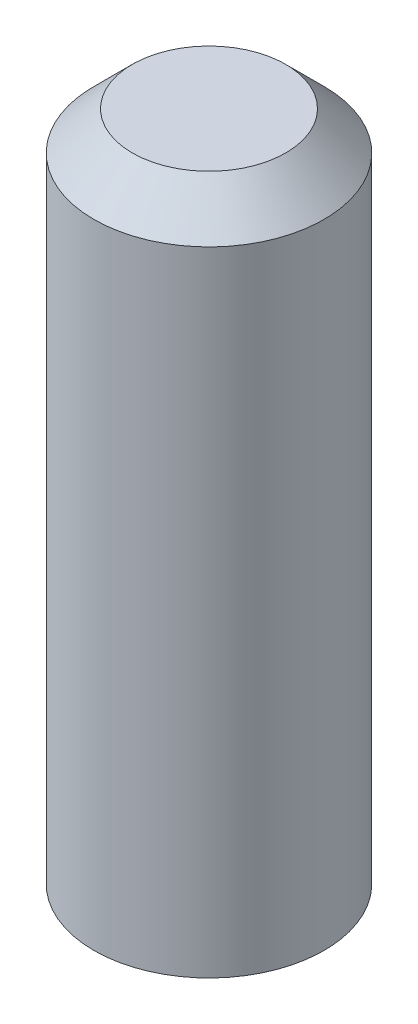
SolidWorks part; units mm, degrees
ref_plane "Plano frontal" through (0, 0, 0) normal (0, 0, 1) x (1, 0, 0)
ref_plane "Plano superior" through (0, 0, 0) normal (0, 1, 0) x (1, 0, 0)
ref_plane "Plano direito" through (0, 0, 0) normal (1, 0, 0) x (0, 0, -1)
sketch "Esboço1" plane through (0, 0, 0) normal (0, 1, 0) x (1, 0, 0)
  circle A0 centre (0, 0) radius 6
  dimension "D1" = 12
extrude "Ressalto-extrusão1" add sketch "Esboço1" along normal blind 35
chamfer "Chanfro1" distance 2 angle 45 1 edges at (0, 35, 6)
sketch "Esboço2" plane through (0, 0, 0) normal (0, -1, 0) x (1, 0, 0)
  circle A0 centre (0, 0) radius 3.4
  dimension "D1" = 6.8
extrude "Corte-extrusão1" cut sketch "Esboço2" against normal blind 25
